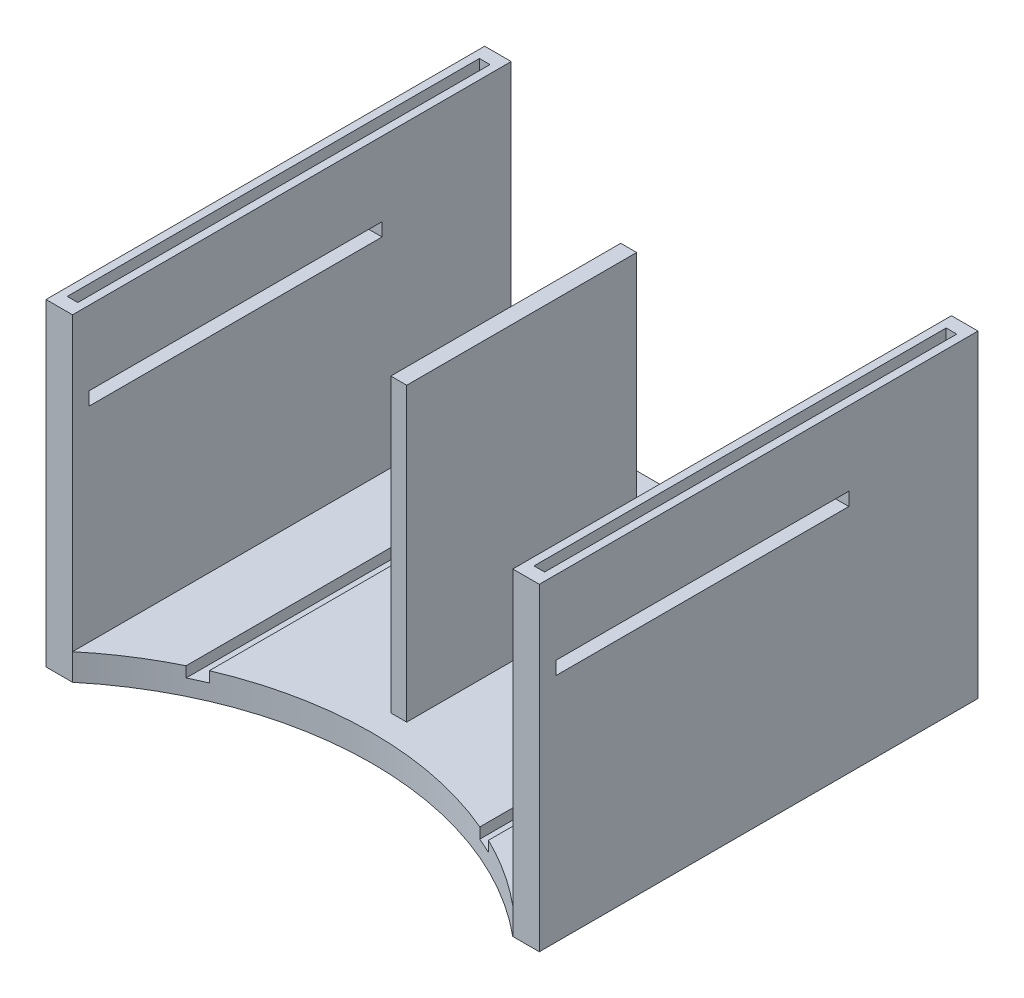
SolidWorks part; units mm, degrees
ref_plane "Front Plane" through (0, 0, 0) normal (0, 0, 1) x (1, 0, 0)
ref_plane "Top Plane" through (0, 0, 0) normal (0, 1, 0) x (1, 0, 0)
ref_plane "Right Plane" through (0, 0, 0) normal (1, 0, 0) x (0, 0, -1)
sketch "Sketch2" plane through (0, 0, 0) normal (0, 0, 1) x (1, 0, 0)
  line L0 (0, 0) -> (186, 0)
  line L1 (186, 0) -> (186, 120)
  line L2 (0, 0) -> (0, 120)
  dimension "D1" = 120
  dimension "D2" = 186
extrude "Extrude-Thin2" add sketch "Sketch2" along normal blind 165.4 thin thin type one direction wall 10
sketch "Sketch11" plane through (0, 10, 0) normal (0, 1, 0) x (1, 0, 0)
  line L0 (10, -165.4) -> (10, 0) construction
  line L1 (10, -32.703) -> (176, -32.703)
  line L2 (10, -32.703) -> (10, -36.703)
  line L3 (10, -36.703) -> (176, -36.703)
  line L4 (176, -32.703) -> (176, -36.703)
  line L6 (176, 0) -> (10, 0) construction
  dimension "D1" = 32.703
  dimension "D2" = 4
  dimension "D3" = 166
  dimension "D4" = 0
extrude "Boss-Extrude3" add sketch "Sketch11" along normal blind 2.6416
sketch "Sketch13" plane through (10, 0, 0) normal (1, 0, 0) x (0, 0, -1)
  line L0 (0, 120) -> (0, 0) construction
  line L1 (-159.195, 92.0516) -> (-48.7, 92.0516)
  line L2 (-159.195, 92.0516) -> (-159.195, 87.0516)
  line L3 (-159.195, 87.0516) -> (-48.7, 87.0516)
  line L4 (-48.7, 92.0516) -> (-48.7, 87.0516)
  line L6 (-165.4, 120) -> (-165.4, 0) construction
  line L7 (-165.4, 120) -> (0, 120) construction
  dimension "D1" = 5
  dimension "D2" = 6.205
  dimension "D3" = 48.7
  dimension "D4" = 27.9484
extrude "Cut-Extrude6" cut sketch "Sketch13" against normal through all both and the other way through all
sketch "Sketch14" plane through (0, 10, 0) normal (0, 1, 0) x (1, 0, 0)
  line L0 (176, -165.4) -> (10, -165.4)
  line L1 (93, -135.4) -> (10, -135.4) construction
  line L2 (10, -165.4) -> (10, -36.703) construction
  arc A0 (10, -165.4) -> (176, -165.4) centre (93, -265.2167) cw
  dimension "D1" = 30
extrude "Cut-Extrude7" cut sketch "Sketch14" against normal through all
sketch "Sketch19" plane through (0, 120, 0) normal (0, 1, 0) x (1, 0, 0)
  line L0 (10, -165.4) -> (10, -36.703) construction
  line L1 (3, -5) -> (7, -5)
  line L2 (3, -5) -> (3, -160.4)
  line L3 (3, -160.4) -> (7, -160.4)
  line L4 (7, -5) -> (7, -160.4)
  line L5 (0, -165.4) -> (0, 0) construction
  line L6 (0, 0) -> (10, 0) construction
  line L7 (0, -165.4) -> (10, -165.4) construction
  point P9 (5, 0)
  point P12 (5, -165.4)
  dimension "D1" = 3
  dimension "D2" = 3
  dimension "D3" = 5
  dimension "D4" = 5
extrude "Cut-Extrude9" cut sketch "Sketch19" against normal blind 10
sketch "Sketch20" plane through (0, 120, 0) normal (0, 1, 0) x (1, 0, 0)
  line L0 (186, -165.4) -> (186, 0) construction
  line L1 (179, -5) -> (183, -5)
  line L2 (179, -5) -> (179, -160.4)
  line L3 (179, -160.4) -> (183, -160.4)
  line L4 (183, -5) -> (183, -160.4)
  line L5 (176, -165.4) -> (176, 0) construction
  line L6 (176, 0) -> (186, 0) construction
  line L7 (176, -165.4) -> (186, -165.4) construction
  point P9 (181, 0)
  point P12 (181, -165.4)
  dimension "D1" = 3
  dimension "D2" = 3
  dimension "D3" = 5
  dimension "D4" = 5
extrude "Cut-Extrude10" cut sketch "Sketch20" against normal blind 10
sketch "Sketch21" plane through (0, 10, 0) normal (0, 1, 0) x (1, 0, 0)
  line L0 (176, -165.4) -> (176, -36.703) construction
  line L1 (90, -38.703) -> (96, -38.703)
  line L2 (90, -38.703) -> (90, -125.4)
  line L3 (90, -125.4) -> (96, -125.4)
  line L4 (96, -38.703) -> (96, -125.4)
  line L5 (10, -165.4) -> (10, 0) construction
  line L7 (10, -159.195) -> (10, -48.7) construction
  line L8 (10, -119.195) -> (176, -119.195) construction
  line L9 (10, -165.4) -> (10, -36.703) construction
  line L10 (0, -165.4) -> (10, -165.4) construction
  line L11 (10, -36.703) -> (176, -36.703) construction
  dimension "D1" = 80
  dimension "D2" = 80
  dimension "D3" = 40
  dimension "D4" = 46.205
  dimension "D5" = 2
extrude "Boss-Extrude4" add sketch "Sketch21" along direction (0, 1, 0) on the side of the normal through all
sketch "Sketch22" plane through (0, 10, 0) normal (0, 1, 0) x (1, 0, 0)
  line L0 (36, -48.703) -> (36, -148.5832)
  line L1 (36, -148.5832) -> (42, -145.8376)
  line L2 (42, -145.8376) -> (42, -48.703)
  line L3 (42, -48.703) -> (36, -48.703)
  line L4 (10, -36.703) -> (176, -36.703) construction
  line L6 (10, -159.195) -> (10, -48.7) construction
  line L7 (144, -145.8376) -> (150, -148.5832)
  line L8 (150, -148.5832) -> (150, -48.703)
  line L9 (150, -48.703) -> (144, -48.703)
  line L10 (144, -48.703) -> (144, -145.8376)
  line L11 (176, -165.4) -> (176, -36.703) construction
  arc A0 (176, -165.4) -> (10, -165.4) centre (93, -265.2167) ccw construction
  dimension "D1" = 6
  dimension "D2" = 26
  dimension "D3" = 6
  dimension "D4" = 26
  dimension "D5" = 12
extrude "Cut-Extrude11" cut sketch "Sketch22" against normal blind 4
sketch "Sketch23" plane through (0, 10, 0) normal (0, 1, 0) x (1, 0, 0)
  line L0 (10, -32.703) -> (10, 0) construction
  line L1 (10, -25.4) -> (176, -25.4)
  line L2 (10, -25.4) -> (10, -29.4)
  line L3 (10, -29.4) -> (176, -29.4)
  line L4 (176, -25.4) -> (176, -29.4)
  line L8 (176, -32.703) -> (10, -32.703) construction
  dimension "D1" = 3.303
  dimension "D2" = 166
  dimension "D3" = 0
  dimension "D4" = 4
extrude "Boss-Extrude5" add sketch "Sketch23" along normal blind 2.6416
sketch "Sketch24" plane through (0, 12.6416, 0) normal (0, 1, 0) x (1, 0, 0)
  line L0 (10, -29.4) -> (176, -29.4) construction
  line L1 (10, -25.4) -> (14.14, -25.4)
  line L2 (10, -25.4) -> (10, -29.4)
  line L3 (10, -29.4) -> (14.14, -29.4)
  line L4 (14.14, -25.4) -> (14.14, -29.4)
  dimension "D1" = 4.14
